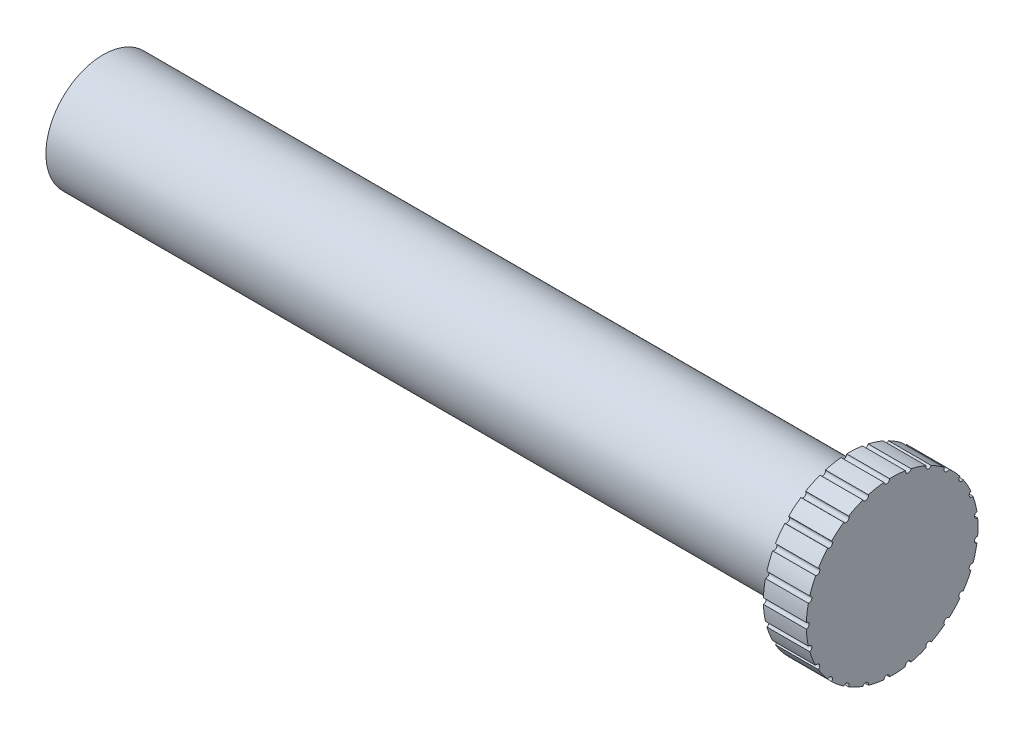
SolidWorks part; units mm, degrees
ref_plane "Front Plane" through (0, 0, 0) normal (0, 0, 1) x (1, 0, 0)
ref_plane "Top Plane" through (0, 0, 0) normal (0, 1, 0) x (1, 0, 0)
ref_plane "Right Plane" through (0, 0, 0) normal (1, 0, 0) x (0, 0, -1)
sketch "Sketch1" plane through (0, 0, 0) normal (1, 0, 0) x (0, 0, -1)
  circle A0 centre (0, 0) radius 4
  dimension "D1" = 8
extrude "Boss-Extrude1" add sketch "Sketch1" along normal blind 52.14
sketch "Sketch2" plane through (52.14, 0, 0) normal (1, 0, 0) x (0, 0, -1)
  circle A0 centre (0, 0) radius 6
  dimension "D1" = 12
extrude "Boss-Extrude2" add sketch "Sketch2" along normal blind 3
sketch "Sketch3" plane through (55.14, 0, 0) normal (1, 0, 0) x (0, 0, -1)
  circle A0 centre (0, 0) radius 6 construction
  circle A1 centre (0, 0) radius 6
  circle A2 centre (-6, 0) radius 0.2
  circle M2 centre (0, 0) radius 6
  dimension "D1" = 0.4
extrude "Cut-Extrude1" cut sketch "Sketch3" against normal up to next contours A2 M2 | A2 M2
pattern_circular "CirPattern1" count 25 every 14.4 about axis through (0, 0, 0) along (1, 0, 0) of "Cut-Extrude1"
